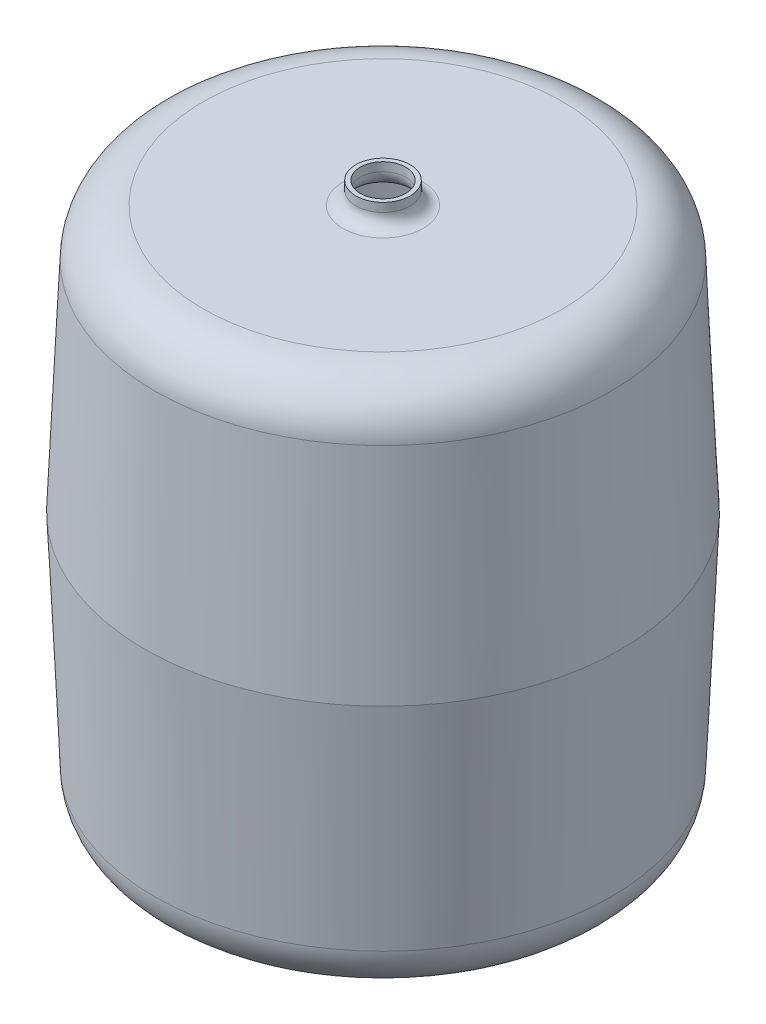
SolidWorks part; units mm, degrees
material "Alliage 1060"
ref_plane "Front Plane" through (0, 0, 0) normal (0, 0, 1) x (1, 0, 0)
ref_plane "Top Plane" through (0, 0, 0) normal (0, 1, 0) x (1, 0, 0)
ref_plane "Right Plane" through (0, 0, 0) normal (1, 0, 0) x (0, 0, -1)
sketch "Sketch1" plane through (0, 0, 0) normal (0, 0, 1) x (1, 0, 0)
  line L0 (0, -5395.1969) -> (0, 264364.6477) construction
  line L1 (0, 0) -> (165.6719, 0)
  line L2 (210.629, 43.0371) -> (219.4469, 245)
  line L3 (219.4469, 245) -> (210.629, 446.9629)
  line L4 (165.6719, 490) -> (37, 490)
  line L5 (25, 502) -> (25, 510)
  line L6 (0, 4) -> (165.6719, 4)
  line L7 (206.6328, 43.2116) -> (215.4431, 245)
  line L8 (215.4431, 245) -> (206.6328, 446.7884)
  line L9 (165.6719, 486) -> (37, 486)
  line L10 (21, 502) -> (21, 510)
  line L11 (21, 510) -> (25, 510)
  line L12 (0, 0) -> (0, 4)
  arc A0 (37, 490) -> (25, 502) centre (37, 502) cw
  arc A1 (165.6719, 0) -> (210.629, 43.0371) centre (165.6719, 45) ccw
  arc A2 (210.629, 446.9629) -> (165.6719, 490) centre (165.6719, 445) ccw
  arc A3 (165.6719, 4) -> (206.6328, 43.2116) centre (165.6719, 45) ccw
  arc A4 (206.6328, 446.7884) -> (165.6719, 486) centre (165.6719, 445) ccw
  arc A5 (37, 486) -> (21, 502) centre (37, 502) cw
  point P11 (25, 490)
  point P14 (208.75, 0)
  dimension "D8" = 12
  dimension "D9" = 45
  dimension "D1" = 208.75
  dimension "D2" = 490
  dimension "D3" = 245
  dimension "D4" = 20
  dimension "D5" = 25
  dimension "D6" = 92.5
  dimension "D7" = 92.5
  dimension "D10" = 4
revolve "Revolve1" add sketch "Sketch1" angle 360 about L0
sketch "Sketch3" plane through (0, 0, 0) normal (0, -1, 0) x (1, 0, 0)
  circle A0 centre (0, 0) radius 153.6719
  circle A1 centre (0, 0) radius 150.6719
  circle A2 centre (0, 0) radius 165.6719 construction
  dimension "D1" = 12
  dimension "D2" = 3
sketch "Sketch4" plane through (0, 490, 0) normal (0, 1, 0) x (1, 0, 0)
  line L0 (0, 0) -> (88.1426, 125.8806) construction
  line L1 (88.1426, 125.8806) -> (0, 0) construction
  line L2 (0, 0) -> (165.6719, 0) construction
  line L3 (165.6719, 0) -> (0, 0) construction
  line L4 (0, 0) -> (88.1426, -125.8806) construction
  line L5 (88.1426, 125.8806) -> (86.4218, 123.4232)
  line L6 (86.4218, -123.4232) -> (88.1426, -125.8806)
  arc A0 (88.1426, 125.8806) -> (88.1426, -125.8806) centre (0, 0) ccw
  arc A1 (86.4218, 123.4232) -> (86.4218, -123.4232) centre (0, 0) ccw
  circle A2 centre (0, 0) radius 165.6719 construction
  point P3 (165.6719, 0)
  dimension "D1" = 12
  dimension "D2" = 3
  dimension "D3" = 55
  dimension "D4" = 55
